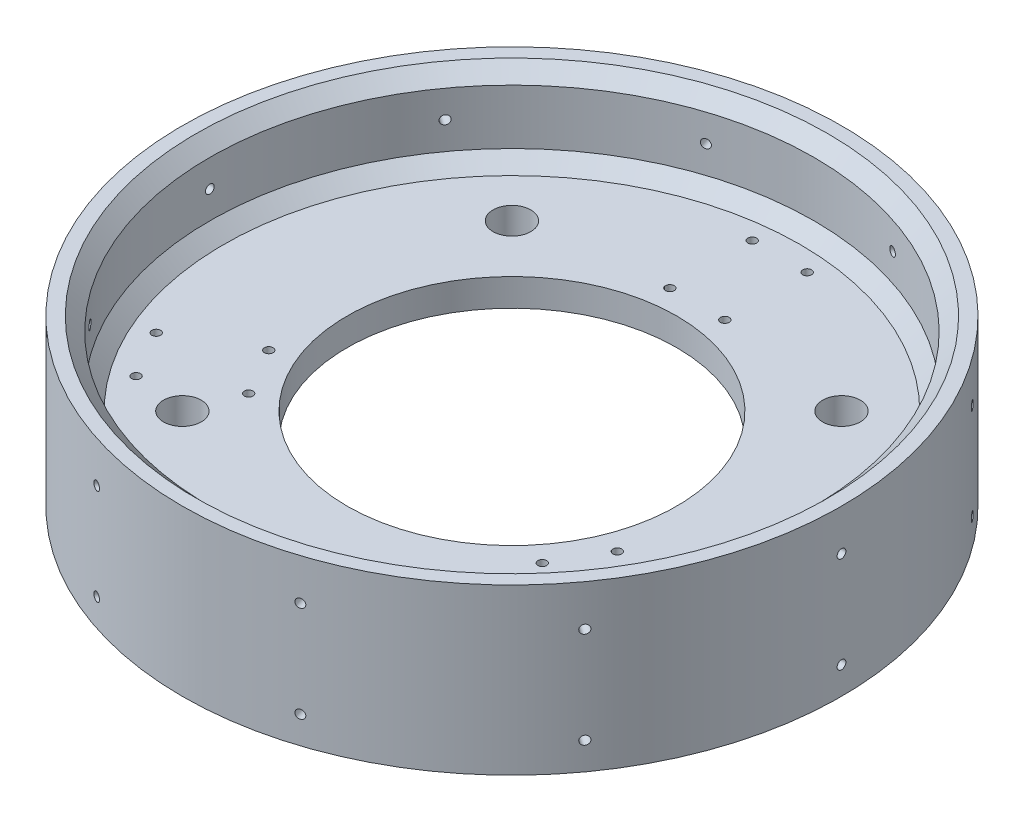
SolidWorks part; units mm, degrees
material "6061-T6 (SS)"
ref_plane "Front Plane" through (0, 0, 0) normal (0, 0, 1) x (1, 0, 0)
ref_plane "Top Plane" through (0, 0, 0) normal (0, 1, 0) x (1, 0, 0)
ref_plane "Right Plane" through (0, 0, 0) normal (1, 0, 0) x (0, 0, -1)
sketch "Sketch1" plane through (0, 0, 0) normal (0, 0, 1) x (1, 0, 0)
  line L0 (76.2, 221.1224) -> (76.2, -116.4364) construction
  line L1 (0, 156.3168) -> (0, -82.2533) construction
  line L2 (-103.9738, 0) -> (210.7963, 0) construction
  line L3 (76.2, 0) -> (139.7, 0)
  line L4 (139.7, 0) -> (139.7, -25.4)
  line L5 (139.7, -25.4) -> (152.4, -25.4)
  line L6 (152.4, -25.4) -> (152.4, 50.8)
  line L7 (152.4, 50.8) -> (139.7, 50.8)
  line L8 (139.7, 50.8) -> (139.7, 12.7)
  line L9 (139.7, 12.7) -> (76.2, 12.7)
  line L10 (76.2, 12.7) -> (76.2, 0)
  point P12 (76.2, 6.35)
  dimension "D1" = 76.2
  dimension "D2" = 76.2
  dimension "D3" = 12.7
  dimension "D4" = 12.7
  dimension "D5" = 25.4
  dimension "D6" = 76.2
revolve "Revolve1" add sketch "Sketch1" angle 360 about L1
chamfer "Chamfer1" distance 6.35 angle 45 4 edges at (0, 50.8, 139.7) (0, -25.4, 139.7) (0, 0, 139.7) (0, 12.7, 139.7)
ref_plane "Plane1" through (152.4, 0, 0) normal (1, 0, 0) x (0, 0, -1)
sketch "Sketch2" plane through (152.4, 0, 0) normal (1, 0, 0) x (0, 0, -1)
  line L0 (0, 76.6667) -> (0, -64.6292) construction
  line L1 (-185.2326, 0) -> (218.1165, 0) construction
  line L2 (-152.4, -25.4) -> (152.4, -25.4) construction
  line L3 (152.4, 50.8) -> (-152.4, 50.8) construction
  line L4 (-152.4, -25.4) -> (152.4, -25.4) construction
  line L5 (152.4, 50.8) -> (-152.4, 50.8) construction
hole_wizard "#10-32 Tapped Hole1" positions "3DSketch1" profile "Sketch3" tap size "#10-32" standard "ANSI Inch"
sketch3d "3DSketch1"
  line L0 (152.4, 76.6667, 0) -> (152.4, -64.6292, 0) construction
  line L1 (152.4, 50.8, -152.4) -> (152.4, 50.8, 152.4) construction
  line L2 (152.4, -25.4, 152.4) -> (152.4, -25.4, -152.4) construction
  point P0 (152.4, 31.75, 0)
  point P2 (152.4, -12.7, 0)
  dimension "D1" = 19.05
  dimension "D2" = 12.7
sketch "Sketch3" plane through (152.4, 31.75, 0) normal (0, 1, 0) x (0, 0, -1)
  line L0 (0, 0) -> (0, 14.9293)
  line L1 (0, 14.9293) -> (2.0193, 13.716)
  line L2 (2.0193, 13.716) -> (2.0193, 0)
  line L5 (2.0193, 0) -> (0, 0)
  line L10 (0, 14.9293) -> (-2.0193, 13.716) construction
  line L11 (0, -6.35) -> (0, 107.95) construction
  dimension "Tap Drill Dia." = 4.0386
  dimension "Tap Drill Depth" = 13.716
  dimension "Drill Angle" = 118
cosmetic thread "Hole Thread1" parameters "D1"=9.652, "D2"=4.826
cosmetic thread "Hole Thread2" parameters "D1"=9.652, "D2"=4.826
pattern_circular "CirPattern1" count 10 over 360 about axis through (0, 156.3168, 0) along (0, 1, 0) of "#10-32 Tapped Hole1"
sketch "Sketch4" plane through (0, 12.7, 0) normal (0, 1, 0) x (1, 0, 0)
  point P0 (-76.2, 76.2)
  point P1 (76.2, 76.2)
  point P2 (76.2, -76.2)
  point P3 (-76.2, -76.2)
  dimension "D1" = 152.4
  dimension "D2" = 152.4
  dimension "D3" = 76.2
  dimension "D4" = 76.2
hole_wizard "3/4-16 Tapped Hole1" positions "3DSketch2" profile "Sketch6" tap size "3/4-16" standard "ANSI Inch" end condition up to next
sketch3d "3DSketch2"
  point P0 (-76.2, 12.7, -76.2)
  point P3 (76.2, 12.7, -76.2)
  point P6 (76.2, 12.7, 76.2)
  point P9 (-76.2, 12.7, 76.2)
sketch "Sketch6" plane through (-76.2, 12.7, -76.2) normal (1, 0, 0) x (0, 0, 1)
  line L0 (0, 0) -> (0, 12.7)
  line L1 (0, 12.7) -> (8.7312, 12.7)
  line L2 (8.7312, 12.7) -> (8.7312, 0)
  line L5 (8.7312, 0) -> (0, 0)
  line L11 (0, -6.35) -> (0, 107.95) construction
  dimension "Thru Tap Drill Dia." = 17.4625
  dimension "Thru Tap Drill Depth" = 12.7
cosmetic thread "Hole Thread3" parameters "D2"=19.05
cosmetic thread "Hole Thread4" parameters "D2"=19.05
cosmetic thread "Hole Thread5" parameters "D2"=19.05
cosmetic thread "Hole Thread6" parameters "D2"=19.05
sketch "Holes for Tang" plane through (0, 12.7, 0) normal (0, 1, 0) x (1, 0, 0)
  line L0 (-160.9641, -92.9327) -> (160.9641, 92.9327) construction
  line L1 (0, 148.761) -> (0, -148.761) construction
  line L2 (-189.7886, 109.5745) -> (189.7886, -109.5745) construction
  line L3 (-100.8856, -72.911) -> (-62.4416, -50.7154) construction
  line L4 (-120.0526, -54.6477) -> (-73.0194, -27.4931) construction
  line L5 (-80.59, -31.864) -> (-67.89, -53.861) construction
  line L6 (-12.7, 129.7327) -> (-12.7, 82.7286) construction
  line L7 (12.7, 132.7439) -> (12.7, 82.7286) construction
  line L8 (12.7, 82.7286) -> (-12.7, 82.7286) construction
  line L9 (78.8359, -30.8512) -> (110.4094, -49.0802) construction
  line L10 (97.2664, -70.8215) -> (67.6742, -53.7364) construction
  line L11 (67.89, -53.861) -> (80.59, -31.864) construction
  circle A0 centre (0, 0) radius 133.35 construction
  circle A1 centre (0, 0) radius 133.35
  circle A2 centre (0, 0) radius 133.35
  point P0 (-113.5856, -50.914)
  point P1 (-80.59, -31.864)
  point P5 (-67.89, -53.861)
  point P6 (-100.8856, -72.911)
  point P19 (-12.7, 123.825)
  point P20 (-12.7, 85.725)
  point P25 (12.7, 85.725)
  point P26 (12.7, 123.825)
  point P29 (113.5856, -50.914)
  point P30 (100.8856, -72.911)
  point P31 (67.89, -53.861)
  point P34 (80.59, -31.864)
  dimension "D2" = 60
  dimension "D3" = 60
  dimension "D4" = 25.4
  dimension "D5" = 12.7
  dimension "D6" = 38.1
  dimension "D7" = 38.1
  dimension "D8" = 85.725
  dimension "D9" = 25.4
  dimension "D10" = 12.7
  dimension "D11" = 38.1
  dimension "D12" = 38.1
  dimension "D13" = 85.725
  dimension "D14" = 25.4
  dimension "D15" = 12.7
  dimension "D16" = 38.1
  dimension "D17" = 38.1
  dimension "D18" = 85.725
  dimension "D1" = 0
hole_wizard "#10-32 Tapped Hole2" positions "3DSketch3" profile "Sketch8" tap size "#10-32" standard "ANSI Inch" end condition up to next
sketch3d "3DSketch3"
  point P0 (-12.7, 12.7, -85.725)
  point P3 (12.7, 12.7, -85.725)
  point P6 (12.7, 12.7, -123.825)
  point P9 (-12.7, 12.7, -123.825)
  point P12 (100.8856, 12.7, 72.911)
  point P15 (113.5856, 12.7, 50.914)
  point P18 (67.89, 12.7, 53.861)
  point P21 (80.59, 12.7, 31.864)
  point P24 (-67.89, 12.7, 53.861)
  point P27 (-80.59, 12.7, 31.864)
  point P30 (-113.5856, 12.7, 50.914)
  point P33 (-100.8856, 12.7, 72.911)
sketch "Sketch8" plane through (-12.7, 12.7, -85.725) normal (1, 0, 0) x (0, 0, 1)
  line L0 (0, 0) -> (0, 12.7)
  line L1 (0, 12.7) -> (2.0193, 12.7)
  line L2 (2.0193, 12.7) -> (2.0193, 0)
  line L5 (2.0193, 0) -> (0, 0)
  line L11 (0, -6.35) -> (0, 107.95) construction
  dimension "Thru Tap Drill Dia." = 4.0386
  dimension "Thru Tap Drill Depth" = 12.7
cosmetic thread "Hole Thread7" parameters "D2"=4.826
cosmetic thread "Hole Thread8" parameters "D2"=4.826
cosmetic thread "Hole Thread9" parameters "D2"=4.826
cosmetic thread "Hole Thread10" parameters "D2"=4.826
cosmetic thread "Hole Thread11" parameters "D2"=4.826
cosmetic thread "Hole Thread12" parameters "D2"=4.826
cosmetic thread "Hole Thread13" parameters "D2"=4.826
cosmetic thread "Hole Thread14" parameters "D2"=4.826
cosmetic thread "Hole Thread15" parameters "D2"=4.826
cosmetic thread "Hole Thread16" parameters "D2"=4.826
cosmetic thread "Hole Thread17" parameters "D2"=4.826
cosmetic thread "Hole Thread18" parameters "D2"=4.826
equation "\"D3@Sketch4\"=\"D1@Sketch4\"/2"
equation "\"D2@Sketch4\"=\"D1@Sketch4\""
equation "\"D4@Sketch4\"=\"D1@Sketch4\"/2"
equation "\"D10@Holes for Tang\" = \"D9@Holes for Tang\" / 2"
equation "\"D12@Holes for Tang\" = \"D11@Holes for Tang\""
